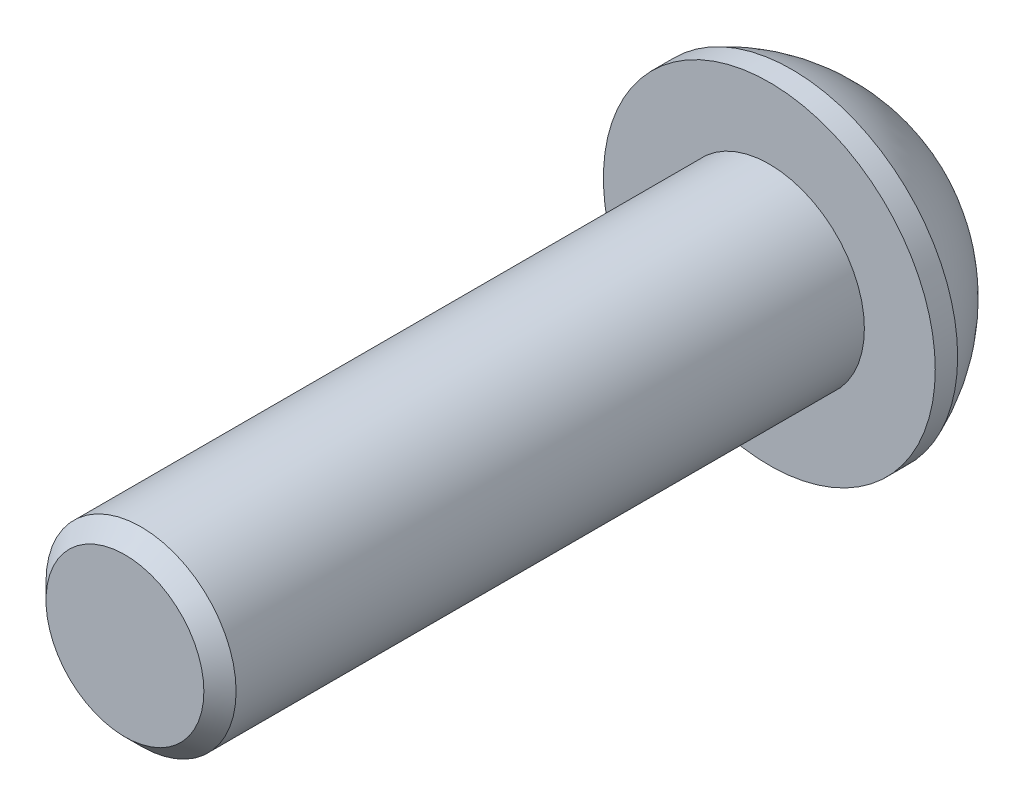
SolidWorks part; units mm, degrees
ref_plane "Front" through (0, 0, 0) normal (0, 0, 1) x (1, 0, 0)
ref_plane "Top" through (0, 0, 0) normal (0, 1, 0) x (1, 0, 0)
ref_plane "Right" through (0, 0, 0) normal (1, 0, 0) x (0, 0, -1)
sketch "Skizze1" plane through (0, 0, 0) normal (0, 0, 1) x (1, 0, 0)
  circle A0 centre (0, 0) radius 2.95
  dimension "D1" = 5.9
extrude "Aufsatz-Linear austragen1" add sketch "Skizze1" along normal blind 20
sketch "Skizze2" plane through (0, 0, 0) normal (1, 0, 0) x (0, 0, -1)
  line L0 (0, 0) -> (0, 5.15)
  line L1 (0, 0) -> (6.2908, 0) construction
  line L2 (3.25, 0) -> (3.25, 3.1)
  line L3 (0, 5.15) -> (0.6952, 5.15)
  line L4 (0, 5.15) -> (0, 5.3818) construction
  line L5 (0, 0) -> (3.25, 0)
  line L6 (3.25, 0) -> (0, 0)
  arc A0 (3.25, 3.1) -> (0.6952, 5.15) centre (-1.4592, -0.1519) ccw
  arc A1 (0.6952, 5.15) -> (0, 5.3818) centre (-1.4592, -0.1519) ccw construction
  dimension "D1" = 3.25
  dimension "D2" = 10.3
  dimension "D3" = 6.2
revolve "Rotation1" add sketch "Skizze2" angle 360 about L1
chamfer "Fase1" distance 0.5 angle 45 1 edges at (2.95, 0, 20)
sketch "Skizze3" plane through (0, 0, -3.25) normal (0, 0, -1) x (-1, 0, 0)
  line L0 (2, 0) -> (0, 0) construction
  line L1 (2, 1.1547) -> (0, 2.3094)
  line L2 (0, 2.3094) -> (-2, 1.1547)
  line L3 (-2, 1.1547) -> (-2, -1.1547)
  line L4 (-2, -1.1547) -> (0, -2.3094)
  line L5 (0, -2.3094) -> (2, -1.1547)
  line L6 (2, -1.1547) -> (2, 1.1547)
  circle A0 centre (0, 0) radius 2 construction
  dimension "D1" = 4
extrude "Schnitt-Linear austragen1" cut sketch "Skizze3" against normal blind 3
